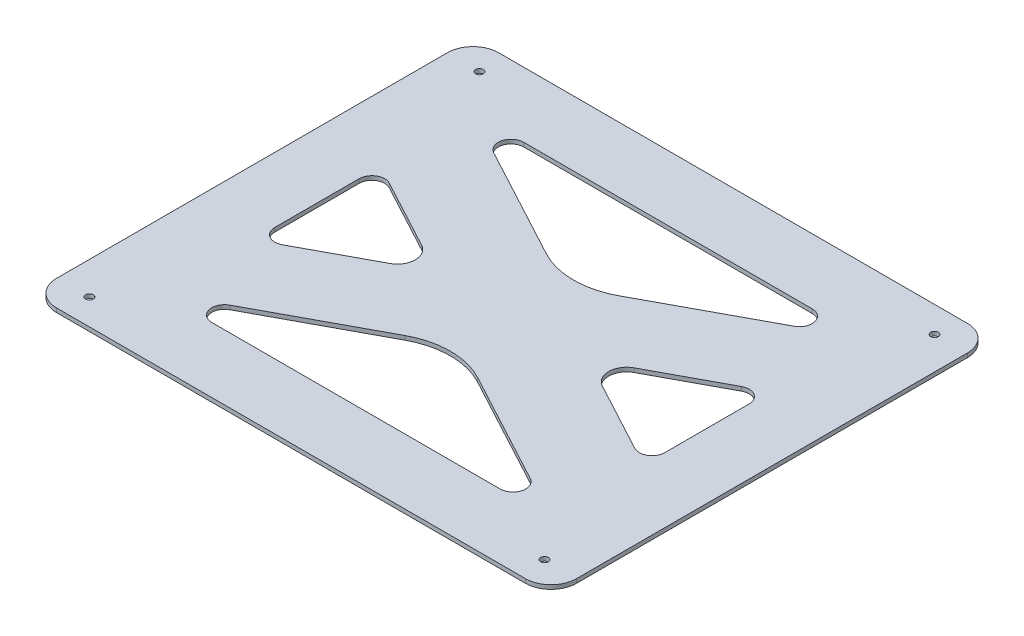
SolidWorks part; units mm, degrees
material "Maple"
ref_plane "Front Plane" through (0, 0, 0) normal (0, 0, 1) x (1, 0, 0)
ref_plane "Top Plane" through (0, 0, 0) normal (0, 1, 0) x (1, 0, 0)
ref_plane "Right Plane" through (0, 0, 0) normal (1, 0, 0) x (0, 0, -1)
sketch "Sketch1" plane through (0, 0, 0) normal (0, 1, 0) x (1, 0, 0)
  line L1 (-101.6, -86.36) -> (101.6, -86.36)
  line L2 (-101.6, -86.36) -> (-101.6, 86.36)
  line L3 (-101.6, 86.36) -> (101.6, 86.36)
  line L4 (101.6, -86.36) -> (101.6, 86.36)
  line L5 (-101.6, -86.36) -> (101.6, 86.36) construction
  line L6 (-101.6, 86.36) -> (101.6, -86.36) construction
  point P0 (0, 0)
  dimension "D1" = 203.2
  dimension "D2" = 172.72
extrude "Boss-Extrude1" add sketch "Sketch1" along normal blind 1.5875
sketch "Sketch2" plane through (0, 1.5875, 0) normal (0, 1, 0) x (1, 0, 0)
  line L0 (-56.3378, 60.96) -> (56.3378, 60.96)
  line L1 (58.7051, 51.5559) -> (14.204, 27.6351)
  line L2 (-14.204, 27.6351) -> (-58.7051, 51.5559)
  line L3 (-56.3378, -60.96) -> (56.3378, -60.96)
  line L4 (58.7051, -51.5559) -> (14.204, -27.6351)
  line L5 (-14.204, -27.6351) -> (-58.7051, -51.5559)
  line L6 (-68.8327, 20.8738) -> (-41.4703, 6.1657)
  line L7 (-41.4703, -6.1657) -> (-68.8327, -20.8738)
  line L8 (-76.2, -16.4698) -> (-76.2, 16.4698)
  line L9 (41.4703, 6.1657) -> (68.8327, 20.8738)
  line L10 (76.2, 16.4698) -> (76.2, -16.4698)
  line L11 (68.8327, -20.8738) -> (41.4703, -6.1657)
  line L12 (101.6, 86.36) -> (-101.6, 86.36) construction
  line L13 (-101.6, -86.36) -> (101.6, -86.36) construction
  line L14 (-101.6, 86.36) -> (-101.6, -86.36) construction
  line L16 (101.6, -86.36) -> (101.6, 86.36) construction
  arc A0 (68.8327, 20.8738) -> (76.2, 16.4698) centre (71.2, 16.4698) cw
  arc A1 (76.2, -16.4698) -> (68.8327, -20.8738) centre (71.2, -16.4698) cw
  arc A2 (56.3378, -60.96) -> (58.7051, -51.5559) centre (56.3378, -55.96) ccw
  arc A3 (-56.3378, -60.96) -> (-58.7051, -51.5559) centre (-56.3378, -55.96) cw
  arc A4 (-68.8327, -20.8738) -> (-76.2, -16.4698) centre (-71.2, -16.4698) cw
  arc A5 (-68.8327, 20.8738) -> (-76.2, 16.4698) centre (-71.2, 16.4698) ccw
  arc A6 (56.3378, 60.96) -> (58.7051, 51.5559) centre (56.3378, 55.96) cw
  arc A7 (-56.3378, 60.96) -> (-58.7051, 51.5559) centre (-56.3378, 55.96) ccw
  arc A8 (14.204, -27.6351) -> (-14.204, -27.6351) centre (0, -54.0595) ccw
  arc A9 (14.204, 27.6351) -> (-14.204, 27.6351) centre (0, 54.0595) cw
  arc A10 (41.4703, 6.1657) -> (41.4703, -6.1657) centre (44.7846, 0) ccw
  arc A11 (-41.4703, 6.1657) -> (-41.4703, -6.1657) centre (-44.7846, 0) cw
  point P21 (0, -24.5163)
  point P22 (0, 13.8234)
  point P23 (-29.5135, 0)
  point P26 (76.2, 24.834)
  point P29 (76.2, -24.834)
  point P32 (76.2, -60.96)
  point P35 (-76.2, -60.96)
  point P38 (-76.2, -24.834)
  point P41 (-76.2, 24.834)
  point P44 (76.2, 60.96)
  point P47 (-76.2, 60.96)
  point P50 (0, -20)
  point P53 (0, 20)
  point P54 (0, 0)
  point P57 (30, 0)
  point P60 (-30, 0)
  dimension "D21" = 5
  dimension "D22" = 30
  dimension "D23" = 7
  dimension "D1" = 25.4
  dimension "D2" = 25.4
  dimension "D3" = 25.4
  dimension "D4" = 0
  dimension "D5" = 360
  dimension "D6" = 0
  dimension "D7" = 25.4
  dimension "D8" = 0
  dimension "D9" = 0
  dimension "D10" = 0
  dimension "D11" = 0
  dimension "D12" = 0
  dimension "D13" = 0
  dimension "D14" = 0
  dimension "D15" = 0
  dimension "D16" = 0
  dimension "D17" = 30
  dimension "D18" = 30
  dimension "D19" = 20
  dimension "D20" = 20
extrude "Cut-Extrude1" cut sketch "Sketch2" against normal blind 1.5875
sketch "Sketch3" plane through (0, 1.5875, 0) normal (0, 1, 0) x (1, 0, 0)
  line L0 (-101.6, 86.36) -> (-101.6, -86.36) construction
  line L1 (-101.6, -86.36) -> (101.6, -86.36) construction
  circle A0 centre (-88.9, 76.2) radius 1.5
  circle A1 centre (88.9, 76.2) radius 1.5
  circle A2 centre (88.9, -76.2) radius 1.5
  circle A3 centre (-88.9, -76.2) radius 1.5
  dimension "D1" = 3
  dimension "D2" = 3
  dimension "D3" = 3
  dimension "D4" = 3
  dimension "D5" = 152.4
  dimension "D7" = 0
  dimension "D8" = 177.8
  dimension "D9" = 12.7
  dimension "D10" = 10.16
  dimension "D6" = 152.4
extrude "Cut-Extrude2" cut sketch "Sketch3" against normal blind 1.5875
fillet "Fillet1" radius 10 4 edges at (-101.6, 0.7937, -86.36) (-101.6, 0.7937, 86.36) (101.6, 0.7937, 86.36) (101.6, 0.7937, -86.36)
